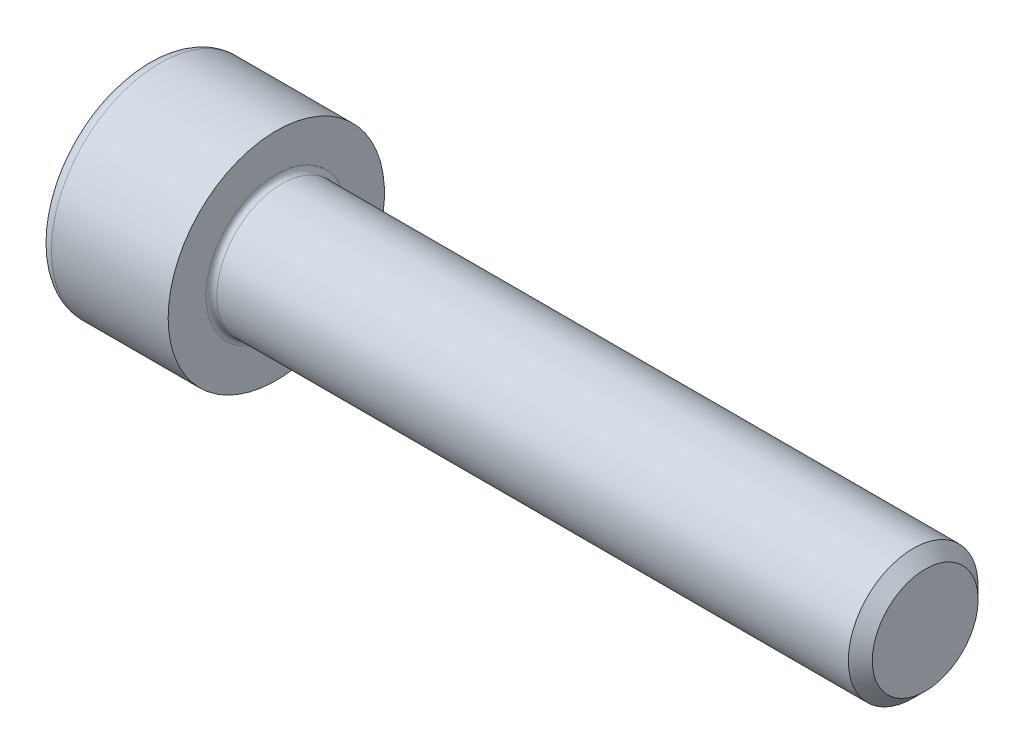
SolidWorks part; units mm, degrees
ref_plane "Plane1" through (0, 0, 0) normal (0, 0, 1) x (1, 0, 0)
ref_plane "Plane2" through (0, 0, 0) normal (0, 1, 0) x (1, 0, 0)
ref_plane "Plane3" through (0, 0, 0) normal (1, 0, 0) x (0, 0, -1)
sketch "BodySke" plane through (0, 0, 0) normal (0, 0, 1) x (1, 0, 0)
  line L0 (0, 0) -> (0, 5)
  line L1 (0, 5) -> (6, 5)
  line L2 (6, 5) -> (6, 3)
  line L3 (6, 3) -> (35.4455, 3)
  line L4 (36, 2.4455) -> (36, 0)
  line L5 (36, 0) -> (0, 0)
  line L6 (-31.75, 0) -> (127, 0) construction
  line L8 (36, 2.4455) -> (35.4455, 3)
  line L10 (36, -2.4455) -> (35.4455, -3) construction
  line L11 (7, 9.525) -> (7, 3.175) construction
  line L12 (12, 9.525) -> (12, 3.175) construction
  line L13 (-24, 9.525) -> (-24, 3.175) construction
  dimension "Diameter" = 6
  dimension "Head_ht" = 6
  dimension "Length" = 30
  dimension "Body_ch_ang" = 45
  dimension "Head_dia" = 10
  dimension "Minor_dia" = 4.891
  dimension "Advance" = 1
  dimension "Thread_nom" = 24
  dimension "Thread_length" = 60
revolve "Base-Revolve" add sketch "BodySke"
cosmetic thread "ThreadCosmetic" [suppressed]
fillet "Fillet1" radius 0.25 1 edges at (6, 0, 3)
fillet "Fillet2" radius 0.6 1 edges at (0, 0, 5)
sketch "Sketch2" plane through (0, 0, 0) normal (0, 0, 1) x (1, 0, 0)
  line L0 (0, 2.51) -> (3, 2.51)
  line L1 (3, 2.51) -> (4.4491, 0)
  line L2 (-31.75, 0) -> (127, 0) construction
  line L3 (4.4491, 0) -> (0, 0)
  line L4 (0, 0) -> (0, 2.51)
  line L6 (0, 0) -> (47.625, 0) construction
  dimension "D1" = 2.51
  dimension "D2" = 60
  dimension "Depth" = 3
revolve "Hex-PreBroach" cut sketch "Sketch2" angle 360 about L6
sketch "Sketch3" plane through (0, 0, 0) normal (-1, 0, 0) x (0, 0.5, 0.866)
  line L0 (1.4491, 2.51) -> (-1.4491, 2.51)
  line L1 (-1.4491, 2.51) -> (-2.8983, 0)
  line L2 (1.4491, 2.51) -> (2.8983, 0)
  line L3 (1.4491, -2.51) -> (2.8983, 0)
  line L4 (1.4491, -2.51) -> (-1.4491, -2.51)
  line L5 (-1.4491, -2.51) -> (-2.8983, 0)
  dimension "D1" = 2.51
  dimension "D2" = 2.51
  dimension "Hex_size" = 5.02
extrude "Hex" cut sketch "Sketch3" against normal blind 3
sketch "ThdSchSke" plane through (0, 0, 0) normal (0, 0, 1) x (1, 0, 0)
  line L0 (12, -2.4455) -> (11.6117, -3)
  line L1 (12, -2.4455) -> (12.3883, -3)
  line L2 (12.3883, -3) -> (12.3883, -3.75)
  line L3 (-3.175, 0) -> (5.1513, 0) construction
  line L4 (0, 4.4) -> (0, -4.4) construction
  line L5 (12.3883, -3.75) -> (11.6117, -3.75)
  line L6 (11.6117, -3.75) -> (11.6117, -3)
  dimension "Thread_minor" = 4.891
  dimension "Diameter" = 6
  dimension "Start" = 12
  dimension "SideAngle" = 55
  dimension "VeeAngle" = 70
  dimension "Overcut" = 7.5
revolve "ThreadSchematic" [suppressed] cut sketch "ThdSchSke" angle 360 about L3
pattern_linear "ThdSchPat" [suppressed]
equation "\"D2@Sketch3\" = \"Hex_size@Sketch3\" / 2"
equation "\"D1@Sketch3\" = \"Hex_size@Sketch3\" / 2"
equation "\"D1@Sketch2\" = \"Hex_size@Sketch3\" / 2"
equation "\"Thread_minor@ThreadCosmetic\"  =  \"Minor_dia@BodySke\""
equation "\"Depth@Sketch2\" =  \"Key_eng@Hex\""
equation "\"Thread_length@ThreadCosmetic\" = ((sgn( (\"Length@BodySke\" - \"Advance@BodySke\" * 3.0) - \"Thread_nom@BodySke\" )-1)*( (\"Length@BodySke\" - \"Advance@BodySke\" * 3.0) - \"Thread_nom@BodySke\" ))/-2+ \"Thread_nom@BodySke\""
equation "\"Thread_minor@ThdSchSke\" = \"Minor_dia@BodySke\""
equation "\"Diameter@ThdSchSke\" = \"Diameter@BodySke\""
equation "\"Overcut@ThdSchSke\" = \"Diameter@BodySke\" * 1.25"
equation "\"Start@ThdSchSke\" = \"Head_ht@BodySke\" + \"Length@BodySke\" - \"Thread_length@ThreadCosmetic\"  '---Non-countersunk---"
equation "\"Num_threads@ThdSchPat\" = int( \"Thread_length@ThreadCosmetic\" / \"Advance@BodySke\" + 0.999 )  + 1"
equation "\"Advance@ThdSchPat\" = \"Thread_length@ThreadCosmetic\" /  (\"Num_threads@ThdSchPat\" - 1) 'relax it"
equation "\"Num_threads@ThdSchPat\" = \"Num_threads@ThdSchPat\" - sgn( \"Num_threads@ThdSchPat\" - 1) '---chamfered tips only---"
